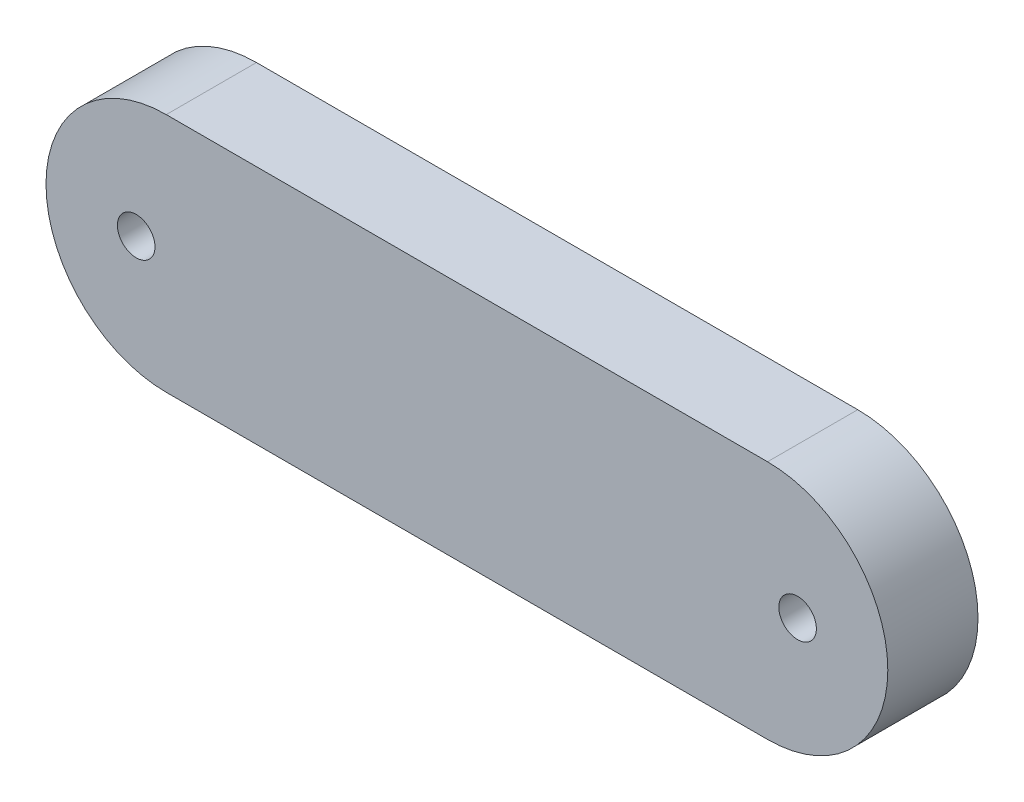
SolidWorks part; units mm, degrees
material "Pine"
ref_plane "Front Plane" through (0, 0, 0) normal (0, 0, 1) x (1, 0, 0)
ref_plane "Top Plane" through (0, 0, 0) normal (0, 1, 0) x (1, 0, 0)
ref_plane "Right Plane" through (0, 0, 0) normal (1, 0, 0) x (0, 0, -1)
sketch "Sketch1" plane through (0, 0, 0) normal (0, 0, 1) x (1, 0, 0)
  line L0 (0, 25.4) -> (0, -25.4) construction
  line L5 (-63.5, -25.4) -> (63.5, -25.4)
  line L6 (-63.5, -25.4) -> (-63.5, 25.4) construction
  line L7 (-63.5, 25.4) -> (63.5, 25.4)
  line L8 (63.5, -25.4) -> (63.5, 25.4) construction
  line L9 (-63.5, -25.4) -> (63.5, 25.4) construction
  line L10 (-63.5, 25.4) -> (63.5, -25.4) construction
  arc A0 (-63.5, 25.4) -> (-63.5, -25.4) centre (-63.5, 0) ccw
  arc A1 (63.5, 25.4) -> (63.5, -25.4) centre (63.5, 0) cw
  circle A2 centre (-69.85, 0) radius 3.9688
  circle A3 centre (69.85, 0) radius 3.9688
  point P0 (0, 0)
  point P7 (-88.9, 0)
  point P9 (88.9, 0)
  dimension "D3" = 7.9375
  dimension "D1" = 177.8
  dimension "D2" = 50.8
  dimension "D4" = 19.05
extrude "Boss-Extrude1" add sketch "Sketch1" along normal mid plane 19.05
